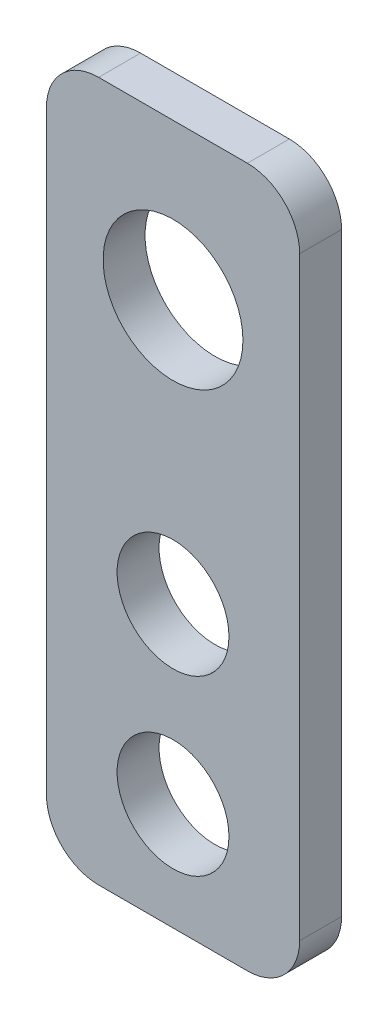
SolidWorks part; units mm, degrees
ref_plane "Front Plane" through (0, 0, 0) normal (0, 0, 1) x (1, 0, 0)
ref_plane "Top Plane" through (0, 0, 0) normal (0, 1, 0) x (1, 0, 0)
ref_plane "Right Plane" through (0, 0, 0) normal (1, 0, 0) x (0, 0, -1)
sketch "Sketch1" plane through (0, 0, 0) normal (0, 0, 1) x (1, 0, 0)
  line L0 (-80.4256, 96.6802) -> (-69.7866, 96.6802)
  line L5 (-66.0503, 100.4166) -> (-66.0503, 142.9723)
  line L6 (-69.7866, 146.7087) -> (-80.4256, 146.7087)
  line L7 (-84.1619, 142.9723) -> (-84.1619, 100.4166)
  line L8 (-84.1619, 121.6945) -> (-66.0503, 121.6945) construction
  line L9 (-75.1061, 96.6802) -> (-75.1061, 163.4051) construction
  arc A0 (-84.1619, 100.4166) -> (-80.4256, 96.6802) centre (-80.4256, 100.4166) ccw
  arc A1 (-69.7866, 96.6802) -> (-66.0503, 100.4166) centre (-69.7866, 100.4166) ccw
  arc A2 (-66.0503, 142.9723) -> (-69.7866, 146.7087) centre (-69.7866, 142.9723) ccw
  arc A3 (-80.4256, 146.7087) -> (-84.1619, 142.9723) centre (-80.4256, 142.9723) ccw
  circle A4 centre (-75.1061, 104.3437) radius 4
  circle A5 centre (-75.1061, 116.7304) radius 4
  circle A6 centre (-75.1061, 135.5798) radius 5
  dimension "D1" = 10
  dimension "D2" = 8
extrude "Boss-Extrude1" add sketch "Sketch1" along normal blind 3
